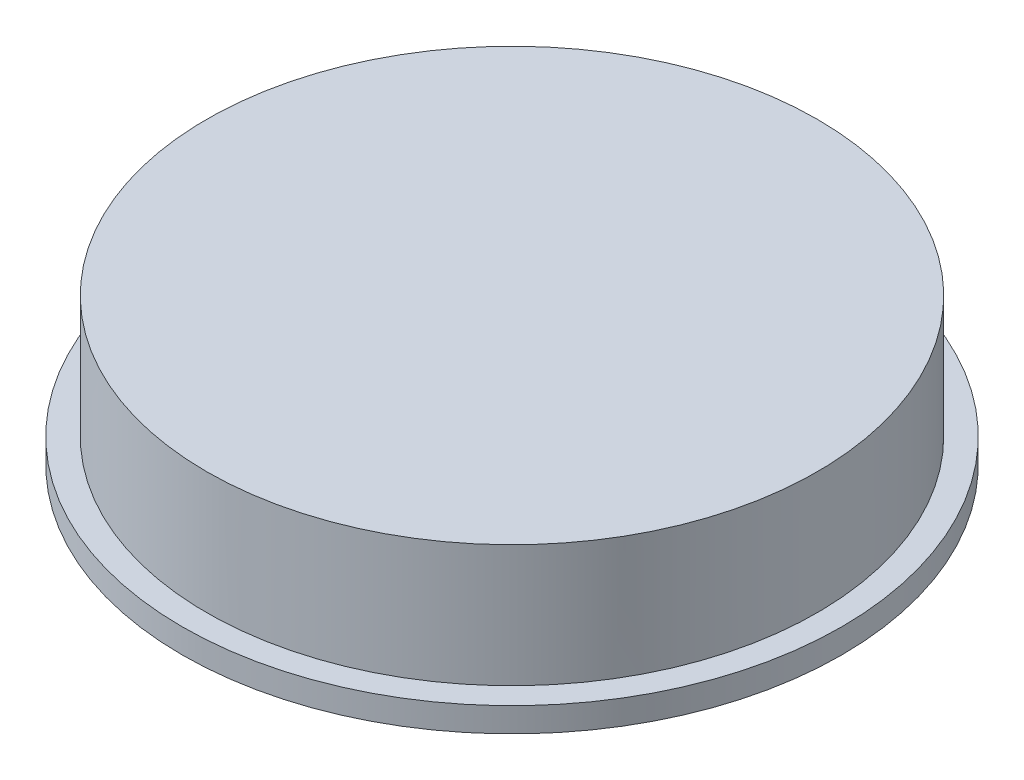
SolidWorks part; units mm, degrees
ref_plane "Front Plane" through (0, 0, 0) normal (0, 0, 1) x (1, 0, 0)
ref_plane "Top Plane" through (0, 0, 0) normal (0, 1, 0) x (1, 0, 0)
ref_plane "Right Plane" through (0, 0, 0) normal (1, 0, 0) x (0, 0, -1)
sketch "Sketch3" plane through (0, 0, 0) normal (0, 1, 0) x (1, 0, 0)
  line L1 (-1.8925, 1.8925) -> (1.8925, 1.8925)
  line L2 (-1.8925, 1.8925) -> (-1.8925, -1.8925)
  line L3 (-1.8925, -1.8925) -> (1.8925, -1.8925)
  line L4 (1.8925, 1.8925) -> (1.8925, -1.8925)
  line L5 (-1.8925, 1.8925) -> (1.8925, -1.8925) construction
  line L6 (-1.8925, -1.8925) -> (1.8925, 1.8925) construction
  line L7 (-3.8925, 3.8925) -> (3.8925, 3.8925)
  line L8 (-3.8925, 3.8925) -> (-3.8925, -3.8925)
  line L9 (-3.8925, -3.8925) -> (3.8925, -3.8925)
  line L10 (3.8925, 3.8925) -> (3.8925, -3.8925)
  line L11 (-3.8925, 3.8925) -> (3.8925, -3.8925) construction
  line L12 (-3.8925, -3.8925) -> (3.8925, 3.8925) construction
  point P0 (0, 0)
  point P6 (0, 0)
  dimension "D1" = 3.785
  dimension "D2" = 2
extrude "Boss-Extrude1" add sketch "Sketch3" along normal blind 4
sketch "Sketch4" plane through (0, 4, 0) normal (0, 1, 0) x (1, 0, 0)
  circle A0 centre (0, 0) radius 12.5
  dimension "D1" = 25
extrude "Boss-Extrude2" add sketch "Sketch4" along normal blind 6
sketch "Sketch5" plane through (0, 4, 0) normal (0, -1, 0) x (1, 0, 0)
  circle A0 centre (0, 0) radius 13.5
  circle A1 centre (0, 0) radius 12.5 construction
  dimension "D1" = 1
extrude "Boss-Extrude3" add sketch "Sketch5" against normal blind 1
fillet "Fillet1" radius 1 4 edges at (3.8925, 2, -3.8925) (-3.8925, 2, -3.8925) (-3.8925, 2, 3.8925) (3.8925, 2, 3.8925)
equation "\"D1@Sketch3\"=3.8-0.015"
